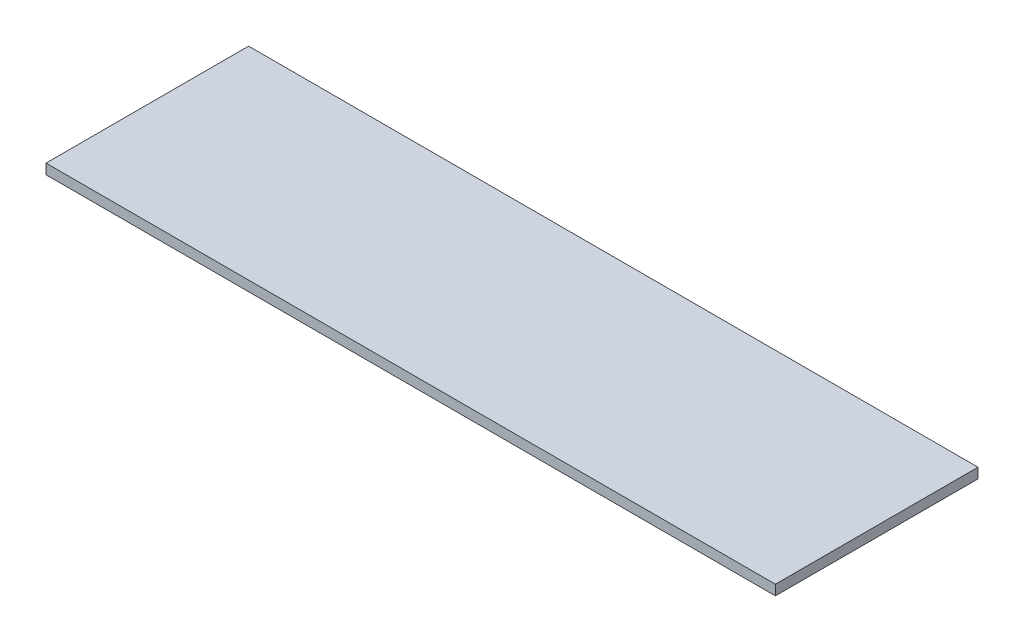
SolidWorks part; units mm, degrees
ref_plane "Alzado" through (0, 0, 0) normal (0, 0, 1) x (1, 0, 0)
ref_plane "Planta" through (0, 0, 0) normal (0, 1, 0) x (1, 0, 0)
ref_plane "Vista lateral" through (0, 0, 0) normal (1, 0, 0) x (0, 0, -1)
sketch "Croquis1" plane through (0, 0, 0) normal (0, 1, 0) x (1, 0, 0)
  line L1 (-360, -100) -> (360, -100)
  line L2 (-360, -100) -> (-360, 100)
  line L3 (-360, 100) -> (360, 100)
  line L4 (360, -100) -> (360, 100)
  line L5 (-360, -100) -> (360, 100) construction
  line L6 (-360, 100) -> (360, -100) construction
  point P0 (0, 0)
  dimension "D1" = 720
  dimension "D2" = 200
extrude "Saliente-Extruir1" add sketch "Croquis1" along normal blind 10
